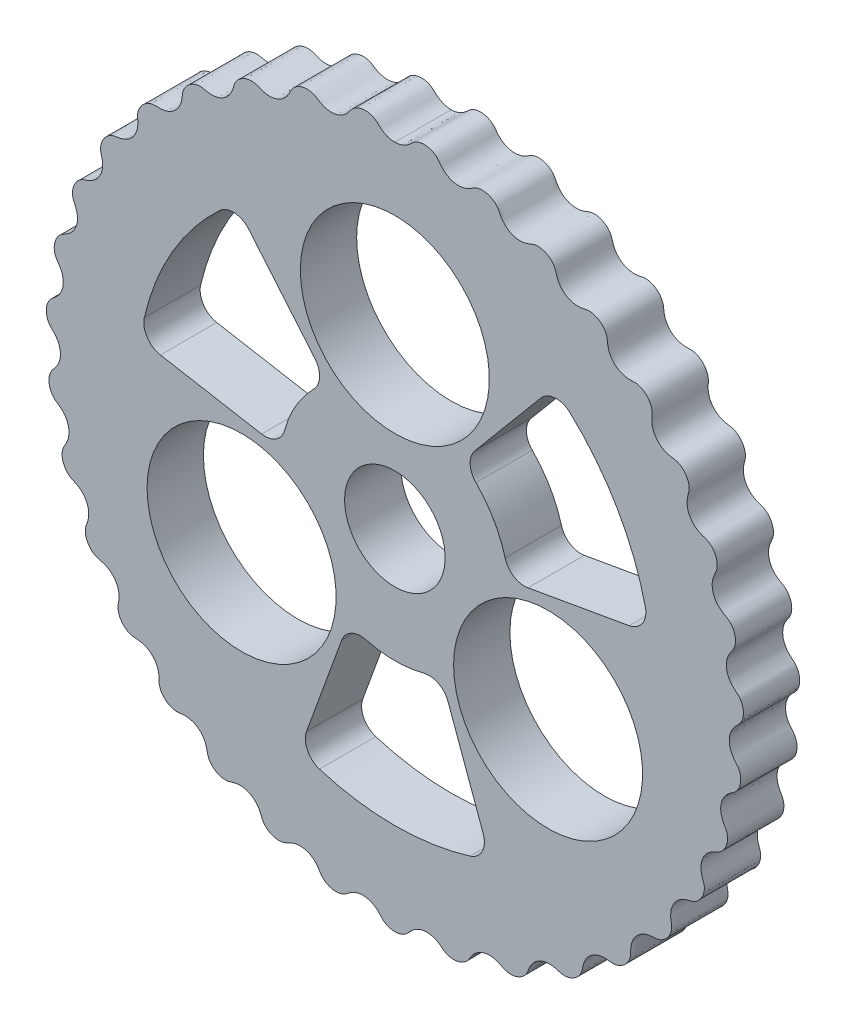
SolidWorks part; units mm, degrees
ref_plane "Plan de face" through (0, 0, 0) normal (0, 0, 1) x (1, 0, 0)
ref_plane "Plan de dessus" through (0, 0, 0) normal (0, 1, 0) x (1, 0, 0)
ref_plane "Plan de droite" through (0, 0, 0) normal (1, 0, 0) x (0, 0, -1)
sketch "Esquisse2" plane through (0, 0, 0) normal (0, 0, 1) x (1, 0, 0)
  line L0 (0, 83.25) -> (0, -86.75) construction
  spline S0 degree 4 poles (-20.3137, 83.5438) (-20.0885, 83.4614) (-19.6527, 83.2536) (-19.0693, 82.8311) (-18.2349, 82.3525) (-17.2735, 81.983) (-16.1925, 81.7883) (-14.9881, 81.8271) (-13.7247, 82.1788) (-12.6769, 82.7766) (-11.9374, 83.4413) (-11.4554, 84.0103) (-11.1542, 84.4115) (-10.918, 84.7359) (-10.664, 85.0472) (-10.378, 85.33) (-9.9202, 85.6954) (-9.2467, 86.0747) (-8.4309, 86.3423) (-7.4979, 86.4492) (-6.664, 86.3976) (-5.946, 86.2408) (-5.3028, 85.9831) (-4.7473, 85.642) (-4.2931, 85.2384) (-3.8888, 84.8455) (-3.459, 84.4786) (-3.0017, 84.147) (-2.5141, 83.861) (-2.0006, 83.6244) (-1.5285, 83.4635) (-1.1447, 83.3693) (-0.8579, 83.3179) (-0.6742, 83.2917) (-0.5261, 83.2749) (-0.3717, 83.2623) (-0.211, 83.2539) (-0.0515, 83.2494) (0.0802, 83.2498) (0.2676, 83.2558) (0.4627, 83.2686) (0.6454, 83.2876) (0.826, 83.313) (1.053, 83.3525) (1.3236, 83.4124) (1.6338, 83.5002) (1.9815, 83.6243) (2.3197, 83.7715) (2.6623, 83.9482) (3.006, 84.1564) (3.3481, 84.3972) (3.686, 84.6706) (4.0086, 84.9618) (4.3218, 85.2626) (4.6475, 85.5509) (5.0042, 85.8008) (5.4202, 86.0257) (5.8955, 86.2129) (6.5687, 86.3866) (7.4412, 86.4615) (8.311, 86.3655) (9.1397, 86.1038) (9.7424, 85.796) (10.151, 85.5199) (10.4937, 85.2237) (10.774, 84.9205) (11.0235, 84.5922) (11.2662, 84.2593) (11.5832, 83.8531) (11.979, 83.4145) (12.4759, 82.9699) (13.2366, 82.4526) (14.2315, 82.004) (15.3166, 81.7873) (16.4255, 81.823) (17.3713, 82.0294) (18.0318, 82.2747) (18.5901, 82.5587) (19.0587, 82.8445) (19.4248, 83.0864) (19.7978, 83.3187) (20.1945, 83.5089) (20.6469, 83.6634) (21.1523, 83.7693) (21.8529, 83.8268) (22.733, 83.7495) (23.5795, 83.5017) (24.3546, 83.0962) (24.9033, 82.6802) (25.2702, 82.3215) (25.5702, 81.9446) (25.8049, 81.5603) (26.0023, 81.1565) (26.2005, 80.7535) (26.4174, 80.3597) (26.6594, 79.9808) (27.0439, 79.4655) (27.6236, 78.8596) (28.4948, 78.2228) (29.5505, 77.786) (30.539, 77.6008) (31.3515, 77.5892) (31.93, 77.6458) (32.4441, 77.746) (32.894, 77.8702) (33.334, 78.0253) (33.7651, 78.2029) (34.194, 78.3861) (34.6387, 78.5298) (35.1344, 78.6217) (35.6743, 78.6503) (36.4031, 78.5923) (37.2755, 78.3642) (38.2058, 77.9072) (38.9618, 77.2791) (39.4472, 76.6783) (39.7362, 76.1701) (39.8957, 75.803) (40.0172, 75.422) (40.1233, 75.037) (40.267, 74.5587) (40.526, 73.8584) (40.9983, 72.9784) (41.7999, 72.0421) (42.9158, 71.2642) (44.0882, 70.8248) (45.0988, 70.6845) (45.9075, 70.7035) (46.5036, 70.779) (46.9756, 70.8691) (47.4431, 70.9783) (47.916, 71.066) (48.4394, 71.0935) (49.0036, 71.044) (49.755, 70.8682) (50.6104, 70.4877) (51.4678, 69.8675) (52.1115, 69.1107) (52.4843, 68.4444) (52.6828, 67.9015) (52.7791, 67.5175) (52.835, 67.1259) (52.8708, 66.7325) (52.9232, 66.2414) (53.0437, 65.5132) (53.3338, 64.5701) (53.9376, 63.4917) (54.7753, 62.62) (55.6308, 62.0456) (56.3655, 61.7153) (56.9231, 61.5369) (57.4475, 61.4244) (57.931, 61.362) (58.4177, 61.3375) (58.9048, 61.3434) (59.3909, 61.3682) (59.8787, 61.3658) (60.3981, 61.2926) (60.9369, 61.1388) (61.6269, 60.8331) (62.3688, 60.3255) (63.0708, 59.6038) (63.5998, 58.7296) (63.8644, 57.9843) (63.9663, 57.3811) (63.9848, 56.947) (63.9698, 56.6) (63.94, 56.2542) (63.9134, 55.9081) (63.8937, 55.4498) (63.9073, 54.879) (63.9959, 54.2007) (64.2091, 53.4336) (64.591, 52.5716) (65.2092, 51.6703) (66.0497, 50.8918) (66.977, 50.3664) (67.7656, 50.0812) (68.3633, 49.9344) (68.8481, 49.8488) (69.3357, 49.7851) (69.8212, 49.7012) (70.3267, 49.5419) (70.8374, 49.2975) (71.4721, 48.8748) (72.1676, 48.1961) (72.7045, 47.3755) (73.0504, 46.4563) (73.181, 45.6819) (73.1929, 45.0999) (73.1234, 44.5605) (72.996, 44.0727) (72.8633, 43.5871) (72.7569, 43.0942) (72.6693, 42.4701) (72.6457, 41.6335) (72.793, 40.5974) (73.2465, 39.4197) (74.0267, 38.3218) (74.9452, 37.5402) (75.8772, 37.0341) (76.7308, 36.7177) (77.4661, 36.5009) (78.227, 36.0981) (78.9429, 35.4726) (79.5823, 34.6046) (79.986, 33.6393) (80.1619, 32.7355) (80.1672, 31.9753) (80.0922, 31.4163) (79.9495, 30.9076) (79.7547, 30.4569) (79.5397, 30.0165) (79.3437, 29.5668) (79.1355, 28.9899) (78.9772, 28.3453) (78.8963, 27.6363) (78.9244, 26.7027) (79.1016, 25.8294) (79.4422, 24.9753) (79.9467, 24.1775) (80.4681, 23.5715) (80.9852, 23.1195) (81.4546, 22.7905) (81.8489, 22.5525) (82.1532, 22.3829) (82.4595, 22.2168) (82.7592, 22.0387) (83.1139, 21.785) (83.5647, 21.3681) (84.0449, 20.7358) (84.4825, 19.819) (84.6995, 18.8474) (84.7206, 17.9654) (84.6084, 17.239) (84.4534, 16.7146) (84.2439, 16.2464) (83.9922, 15.8394) (83.7098, 15.4544) (83.4372, 15.0623) (83.1871, 14.6551) (82.9678, 14.2304) (82.7606, 13.7358) (82.5854, 13.1672) (82.4336, 12.3496) (82.4248, 11.2888) (82.6839, 10.0825) (83.2529, 8.9651) (83.8789, 8.1973) (84.4206, 7.6917) (84.8024, 7.3755) (85.1123, 7.1282) (85.4105, 6.8662) (85.6804, 6.5746) (86.0275, 6.1096) (86.3818, 5.43) (86.6614, 4.475) (86.7087, 3.4173) (86.5573, 2.4948) (86.2931, 1.7725) (86.0266, 1.2751) (85.7184, 0.8535) (85.3873, 0.5069) (85.0398, 0.1781) (84.7049, -0.1641) (84.3133, -0.6169) (83.8506, -1.2769) (83.4074, -2.192) (83.1244, -3.3945) (83.1444, -4.7249) (83.4597, -5.8989) (83.9124, -6.7793) (84.3511, -7.3969) (84.6875, -7.8056) (84.9662, -8.124) (85.2344, -8.4522) (85.4662, -8.8075) (85.6709, -9.2162) (85.8377, -9.6771) (85.9878, -10.322) (86.047, -11.1841) (85.9354, -12.0584) (85.6498, -12.9043) (85.2998, -13.5432) (84.9814, -13.9777) (84.6345, -14.341) (84.2723, -14.6339) (83.885, -14.8907) (83.5002, -15.1509) (83.1287, -15.4306) (82.7773, -15.7351) (82.4101, -16.1059) (82.0431, -16.554) (81.6029, -17.2336) (81.189, -18.1997) (80.9597, -19.4168) (81.0484, -20.5804) (81.2942, -21.4613) (81.5488, -22.0703) (81.7297, -22.4376) (81.929, -22.7949) (82.1387, -23.1461) (82.3387, -23.5033) (82.5022, -23.8792) (82.6351, -24.3087) (82.724, -24.79) (82.7659, -25.4603) (82.6773, -26.3225) (82.4205, -27.159) (82.0044, -27.9321) (81.5737, -28.4843) (81.2095, -28.8478) (80.834, -29.1409) (80.4591, -29.3683) (80.0618, -29.5526) (79.6595, -29.7239) (79.2631, -29.9093) (78.8776, -30.1167) (78.4425, -30.3907) (77.9727, -30.7497) (77.3572, -31.343) (76.7116, -32.2435) (76.2188, -33.4327) (76.0726, -34.6266) (76.144, -35.5492) (76.2791, -36.2031) (76.3885, -36.6023) (76.5195, -36.9948) (76.6639, -37.3823) (76.8021, -37.7723) (76.9032, -38.1743) (76.9638, -38.6249) (76.971, -39.1198) (76.8975, -39.7951) (76.661, -40.6325) (76.2634, -41.4121) (75.7225, -42.0992) (75.2099, -42.5651) (74.7944, -42.8591) (74.3799, -43.0835) (73.9771, -43.2449) (73.5589, -43.3593) (73.1368, -43.4547) (72.6123, -43.5889) (71.8522, -43.8423) (70.9026, -44.3287) (69.8838, -45.1952) (69.1571, -46.2806) (68.7651, -47.3249) (68.5949, -48.2706) (68.5678, -48.9695) (68.614, -49.5897) (68.6948, -50.1288) (68.7733, -50.5574) (68.8365, -50.9892) (68.8509, -51.426) (68.8113, -51.899) (68.7071, -52.401) (68.4823, -53.0616) (68.0653, -53.8328) (67.5073, -54.507) (66.8344, -55.0551) (66.2488, -55.389) (65.7956, -55.579) (65.3619, -55.7031) (64.9562, -55.7722) (64.4439, -55.8074) (63.9312, -55.828) (63.4201, -55.8845) (62.6688, -56.03) (61.7962, -56.3159) (60.778, -56.89) (59.8937, -57.7585) (59.3216, -58.6389) (59.0023, -59.3799) (58.8341, -59.9319) (58.7296, -60.4413) (58.6711, -60.9009) (58.6439, -61.3634) (58.6396, -61.8262) (58.6376, -62.2894) (58.5904, -62.7511) (58.4766, -63.2384) (58.2881, -63.7411) (57.9471, -64.3818) (57.3976, -65.084) (56.7284, -65.6575) (55.9745, -66.0819) (55.3505, -66.311) (54.8718, -66.4244) (54.416, -66.4769) (53.9901, -66.477) (53.567, -66.4322) (53.1461, -66.375) (52.6175, -66.3205) (52.0248, -66.3026) (51.3715, -66.3529) (50.5067, -66.5334) (49.5592, -66.8996) (48.7021, -67.46) (47.9831, -68.1872) (47.5234, -68.843) (47.247, -69.3482) (47.041, -69.8278) (46.8903, -70.2713) (46.772, -70.7243) (46.6788, -71.1829) (46.5972, -71.6436) (46.4812, -72.0978) (46.2921, -72.5712) (46.0218, -73.0501) (45.5688, -73.6459) (44.8902, -74.2638) (43.9891, -74.7977) (42.9475, -75.1154) (42.0775, -75.1772) (41.3992, -75.0867) (40.9195, -74.953) (40.5411, -74.8303) (40.0648, -74.6861) (39.341, -74.5146) (38.3509, -74.4195) (37.0745, -74.5714) (35.8887, -75.0526) (34.9757, -75.6992) (34.3645, -76.3343) (33.9963, -76.8217) (33.7177, -77.2755) (33.5091, -77.6793) (33.327, -78.0958) (33.1647, -78.5199) (33.0016, -78.9441) (32.7967, -79.3507) (32.5228, -79.7583) (32.1761, -80.1551) (31.6425, -80.6272) (30.8921, -81.09) (29.9399, -81.4439) (28.9825, -81.5629) (28.2239, -81.5097) (27.6629, -81.3793) (27.2901, -81.2504) (26.933, -81.0836) (26.5861, -80.8976) (26.1493, -80.6708) (25.4789, -80.3691) (24.5372, -80.0882) (23.3077, -79.9908) (22.1183, -80.2017) (21.1643, -80.5936) (20.3752, -81.0873) (19.8323, -81.5467) (19.3853, -82.0342) (19.0215, -82.5253) (18.7561, -82.936) (18.5081, -83.3567) (18.2383, -83.7651) (17.8918, -84.1612) (17.4665, -84.529) (16.8302, -84.9398) (16.0633, -85.2546) (15.2201, -85.4334) (14.328, -85.4518) (13.5689, -85.3442) (12.873, -85.1185) (12.2622, -84.7834) (11.7499, -84.3712) (11.2593, -83.9912) (10.7379, -83.6518) (10.1856, -83.3662) (9.6051, -83.1421) (9.0031, -82.9846) (8.2142, -82.8724) (7.4052, -82.8868) (6.5996, -83.0341) (5.7411, -83.3421) (5.1148, -83.6737) (4.5689, -84.0602) (4.0996, -84.4775) (3.749, -84.8375) (3.4186, -85.2151) (3.0815, -85.5878) (2.7318, -85.8864) (2.3863, -86.1168) (2.0591, -86.2923) (1.7595, -86.4244) (1.4896, -86.5202) (1.2539, -86.5885) (1.015, -86.6458) (0.8135, -86.6843) (0.6149, -86.7138) (0.4086, -86.7342) (0.2334, -86.745) (0.0699, -86.7503) (-0.0518, -86.7505) (-0.2345, -86.7452) (-0.4665, -86.7309) (-0.6728, -86.7064) (-0.8821, -86.6716) (-1.0908, -86.6285) (-1.2978, -86.5772) (-1.5354, -86.5051) (-1.8017, -86.4061) (-2.0878, -86.278) (-2.3893, -86.1144) (-2.6994, -85.9078) (-3.0086, -85.6504) (-3.2886, -85.3621) (-3.5528, -85.06) (-3.8894, -84.6877) (-4.299, -84.2858) (-4.8034, -83.8813) (-5.5626, -83.4161) (-6.4905, -83.0419) (-7.6131, -82.8396) (-8.8327, -82.9146) (-9.796, -83.1878) (-10.535, -83.5359) (-11.0755, -83.8686) (-11.488, -84.165) (-11.8837, -84.482) (-12.2887, -84.7889) (-12.7554, -85.052) (-13.2795, -85.2553) (-14.0025, -85.4253) (-14.8826, -85.47) (-15.8646, -85.3259) (-16.8095, -84.96) (-17.5493, -84.4853) (-18.0552, -83.9977) (-18.369, -83.5763) (-18.6423, -83.1296) (-18.8229, -82.8307) (-18.9676, -82.6125) (-19.0683, -82.4698) knots 0 0 0 0 0 0.002755 0.005511 0.008266 0.011022 0.014533 0.018044 0.021993 0.025941 0.028246 0.029399 0.030552 0.031705 0.032857 0.03401 0.035163 0.038424 0.041684 0.043786 0.045887 0.047989 0.050091 0.051711 0.053332 0.054953 0.056574 0.058195 0.059815 0.061436 0.063057 0.063918 0.064349 0.064779 0.06521 0.06564 0.066071 0.066501 0.067031 0.06756 0.06809 0.068619 0.069149 0.069678 0.070737 0.071796 0.072855 0.073914 0.074973 0.07622 0.077468 0.078716 0.079964 0.081212 0.08246 0.083707 0.084955 0.086635 0.088314 0.091673 0.094958 0.096601 0.098243 0.099427 0.100611 0.101794 0.102978 0.104162 0.105346 0.107713 0.109756 0.111799 0.115885 0.120169 0.122311 0.124453 0.126974 0.128235 0.129496 0.130757 0.132018 0.133278 0.134539 0.136237 0.137935 0.141332 0.144631 0.14628 0.14793 0.14922 0.150511 0.151801 0.153092 0.154382 0.155673 0.156963 0.158253 0.161762 0.16527 0.169256 0.171249 0.173242 0.174582 0.175921 0.17726 0.1786 0.179939 0.181278 0.182618 0.183957 0.185715 0.187473 0.19099 0.194252 0.197514 0.198662 0.199809 0.200957 0.202104 0.203252 0.204399 0.206694 0.210675 0.214655 0.218407 0.222158 0.224917 0.226297 0.227676 0.229056 0.230435 0.231815 0.233194 0.235058 0.236921 0.240648 0.243874 0.247099 0.248234 0.249369 0.250503 0.251638 0.252773 0.253908 0.256178 0.26011 0.264043 0.267959 0.269917 0.271876 0.273274 0.274673 0.276071 0.27747 0.278869 0.280267 0.281666 0.283065 0.284875 0.286686 0.290307 0.293323 0.29634 0.298334 0.299331 0.300328 0.301325 0.302322 0.303319 0.304316 0.306595 0.308874 0.311153 0.313432 0.317388 0.321344 0.32417 0.325583 0.326996 0.328409 0.329822 0.331235 0.332648 0.334478 0.336307 0.339965 0.343736 0.345621 0.347507 0.348954 0.350401 0.351847 0.353294 0.354741 0.356188 0.359082 0.362879 0.366677 0.370538 0.374399 0.376596 0.378794 0.380991 0.383188 0.386406 0.389624 0.39327 0.395093 0.396916 0.398324 0.399733 0.401141 0.402549 0.403957 0.405366 0.408182 0.410154 0.412125 0.416068 0.418356 0.420644 0.422932 0.42522 0.426221 0.427222 0.428222 0.429223 0.430224 0.431224 0.433226 0.436254 0.439282 0.442804 0.444566 0.446327 0.447698 0.44907 0.450441 0.451813 0.453184 0.454556 0.455927 0.457299 0.459338 0.461377 0.465456 0.469405 0.473353 0.475631 0.47677 0.477909 0.479048 0.480187 0.481326 0.482465 0.485703 0.48894 0.492655 0.494512 0.496369 0.497743 0.499118 0.500493 0.501867 0.503242 0.504617 0.507366 0.511104 0.514843 0.518671 0.522499 0.524931 0.526147 0.527363 0.528578 0.529794 0.53101 0.532226 0.533819 0.535413 0.538599 0.542103 0.543855 0.545607 0.546941 0.548276 0.549611 0.550945 0.55228 0.553614 0.554949 0.556283 0.558269 0.560256 0.564228 0.568282 0.572336 0.573512 0.574687 0.575862 0.577037 0.578212 0.579387 0.580562 0.581737 0.583367 0.584997 0.588257 0.591641 0.593333 0.595025 0.596281 0.597538 0.598794 0.600051 0.601307 0.602564 0.60382 0.605077 0.607211 0.609344 0.613612 0.617714 0.621816 0.623004 0.624192 0.62538 0.626569 0.627757 0.628945 0.630133 0.631321 0.63297 0.634618 0.637915 0.641262 0.642935 0.644609 0.645852 0.647096 0.648339 0.649583 0.650826 0.65207 0.654557 0.658777 0.662996 0.667248 0.669374 0.671499 0.674004 0.675256 0.676508 0.67776 0.679012 0.680264 0.681517 0.683202 0.684888 0.68826 0.691532 0.693168 0.694804 0.695984 0.697163 0.698343 0.699522 0.701881 0.70306 0.70424 0.70831 0.71238 0.716338 0.718317 0.720297 0.721626 0.722956 0.724286 0.725616 0.726945 0.728275 0.729605 0.730935 0.732681 0.734426 0.737918 0.741116 0.742715 0.744314 0.745535 0.746756 0.747976 0.749197 0.750417 0.751638 0.754079 0.756001 0.757922 0.761765 0.765682 0.76764 0.769599 0.770943 0.772287 0.773631 0.774975 0.776319 0.777663 0.779007 0.780351 0.782157 0.783963 0.787576 0.790826 0.794076 0.796362 0.797506 0.798649 0.799792 0.800935 0.803222 0.807186 0.811151 0.815545 0.817743 0.81994 0.821245 0.822549 0.823854 0.825159 0.826464 0.827768 0.829073 0.830378 0.832092 0.833806 0.837234 0.840447 0.84366 0.844791 0.845922 0.847052 0.848183 0.849314 0.850445 0.852706 0.856622 0.860539 0.864468 0.866433 0.868398 0.871205 0.872608 0.874012 0.875415 0.876819 0.878222 0.879626 0.881442 0.883259 0.886893 0.889085 0.891277 0.89347 0.895662 0.897445 0.899228 0.901012 0.902795 0.904578 0.906362 0.908145 0.909928 0.913714 0.915606 0.917499 0.920383 0.921825 0.923267 0.924709 0.926151 0.927592 0.929034 0.929974 0.930914 0.931853 0.932793 0.933263 0.933732 0.934672 0.935142 0.935612 0.936081 0.936551 0.936959 0.937367 0.938182 0.938997 0.939405 0.939812 0.940628 0.941443 0.942258 0.943074 0.944227 0.94538 0.946533 0.947686 0.948839 0.949992 0.952298 0.954273 0.956247 0.960196 0.963723 0.967249 0.970164 0.971621 0.973078 0.974536 0.975993 0.97745 0.978908 0.980669 0.982431 0.985955 0.988966 0.991977 0.993983 0.995988 0.996991 0.997994 1 1 1 1 1 construction
  spline S1 degree 4 poles (0, 83.25) (0.0401, 83.25) (0.1201, 83.2511) (0.2676, 83.2558) (0.4627, 83.2686) (0.6454, 83.2876) (0.826, 83.313) (1.053, 83.3525) (1.3236, 83.4124) (1.6338, 83.5002) (1.9815, 83.6243) (2.3197, 83.7715) (2.6623, 83.9482) (3.006, 84.1564) (3.3481, 84.3972) (3.686, 84.6706) (4.0086, 84.9618) (4.3218, 85.2626) (4.6475, 85.5509) (5.0042, 85.8008) (5.4202, 86.0257) (5.8955, 86.2129) (6.5687, 86.3866) (7.4412, 86.4615) (8.311, 86.3655) (9.1397, 86.1038) (9.7424, 85.796) (10.151, 85.5199) (10.4937, 85.2237) (10.774, 84.9205) (11.0235, 84.5922) (11.2662, 84.2593) (11.5832, 83.8531) (11.979, 83.4145) (12.4759, 82.9699) (13.2366, 82.4526) (14.2315, 82.004) (15.3166, 81.7873) (16.4255, 81.823) (17.3713, 82.0294) (18.0318, 82.2747) (18.5901, 82.5587) (19.0587, 82.8445) (19.4248, 83.0864) (19.7978, 83.3187) (20.1945, 83.5089) (20.6469, 83.6634) (21.1523, 83.7693) (21.8529, 83.8268) (22.733, 83.7495) (23.5795, 83.5017) (24.3546, 83.0962) (24.9033, 82.6802) (25.2702, 82.3215) (25.5702, 81.9446) (25.8049, 81.5603) (26.0023, 81.1565) (26.2005, 80.7535) (26.4174, 80.3597) (26.6594, 79.9808) (27.0439, 79.4655) (27.6236, 78.8596) (28.4948, 78.2228) (29.5505, 77.786) (30.539, 77.6008) (31.3515, 77.5892) (31.93, 77.6458) (32.4441, 77.746) (32.894, 77.8702) (33.334, 78.0253) (33.7651, 78.2029) (34.194, 78.3861) (34.6387, 78.5298) (35.1344, 78.6217) (35.6743, 78.6503) (36.4031, 78.5923) (37.2755, 78.3642) (38.2058, 77.9072) (38.9618, 77.2791) (39.4472, 76.6783) (39.7362, 76.1701) (39.8957, 75.803) (40.0172, 75.422) (40.1233, 75.037) (40.267, 74.5587) (40.526, 73.8584) (40.9983, 72.9784) (41.7999, 72.0421) (42.9158, 71.2642) (44.0882, 70.8248) (45.0988, 70.6845) (45.9075, 70.7035) (46.5036, 70.779) (46.9756, 70.8691) (47.4431, 70.9783) (47.916, 71.066) (48.4394, 71.0935) (49.0036, 71.044) (49.755, 70.8682) (50.6104, 70.4877) (51.4678, 69.8675) (52.1115, 69.1107) (52.4843, 68.4444) (52.6828, 67.9015) (52.7791, 67.5175) (52.835, 67.1259) (52.8708, 66.7325) (52.9232, 66.2414) (53.0437, 65.5132) (53.3338, 64.5701) (53.9376, 63.4917) (54.7753, 62.62) (55.6308, 62.0456) (56.3655, 61.7153) (56.9231, 61.5369) (57.4475, 61.4244) (57.931, 61.362) (58.4177, 61.3375) (58.9048, 61.3434) (59.3909, 61.3682) (59.8787, 61.3658) (60.3981, 61.2926) (60.9369, 61.1388) (61.6269, 60.8331) (62.3688, 60.3255) (63.0708, 59.6038) (63.5998, 58.7296) (63.8644, 57.9843) (63.9663, 57.3811) (63.9848, 56.947) (63.9698, 56.6) (63.94, 56.2542) (63.9134, 55.9081) (63.8937, 55.4498) (63.9073, 54.879) (63.9959, 54.2007) (64.2091, 53.4336) (64.591, 52.5716) (65.2092, 51.6703) (66.0497, 50.8918) (66.977, 50.3664) (67.7656, 50.0812) (68.3633, 49.9344) (68.8481, 49.8488) (69.3357, 49.7851) (69.8212, 49.7012) (70.3267, 49.5419) (70.8374, 49.2975) (71.4721, 48.8748) (72.1676, 48.1961) (72.7045, 47.3755) (73.0504, 46.4563) (73.181, 45.6819) (73.1929, 45.0999) (73.1234, 44.5605) (72.996, 44.0727) (72.8633, 43.5871) (72.7569, 43.0942) (72.6693, 42.4701) (72.6457, 41.6335) (72.793, 40.5974) (73.2465, 39.4197) (74.0267, 38.3218) (74.9452, 37.5402) (75.8772, 37.0341) (76.7308, 36.7177) (77.4661, 36.5009) (78.227, 36.0981) (78.9429, 35.4726) (79.5823, 34.6046) (79.986, 33.6393) (80.1619, 32.7355) (80.1672, 31.9753) (80.0922, 31.4163) (79.9495, 30.9076) (79.7547, 30.4569) (79.5397, 30.0165) (79.3437, 29.5668) (79.1355, 28.9899) (78.9772, 28.3453) (78.8963, 27.6363) (78.9244, 26.7027) (79.1016, 25.8294) (79.4422, 24.9753) (79.9467, 24.1775) (80.4681, 23.5715) (80.9852, 23.1195) (81.4546, 22.7905) (81.8489, 22.5525) (82.1532, 22.3829) (82.4595, 22.2168) (82.7592, 22.0387) (83.1139, 21.785) (83.5647, 21.3681) (84.0449, 20.7358) (84.4825, 19.819) (84.6995, 18.8474) (84.7206, 17.9654) (84.6084, 17.239) (84.4534, 16.7146) (84.2439, 16.2464) (83.9922, 15.8394) (83.7098, 15.4544) (83.4372, 15.0623) (83.1871, 14.6551) (82.9678, 14.2304) (82.7606, 13.7358) (82.5854, 13.1672) (82.4336, 12.3496) (82.4248, 11.2888) (82.6839, 10.0825) (83.2529, 8.9651) (83.8789, 8.1973) (84.4206, 7.6917) (84.8024, 7.3755) (85.1123, 7.1282) (85.4105, 6.8662) (85.6804, 6.5746) (86.0275, 6.1096) (86.3818, 5.43) (86.6614, 4.475) (86.7087, 3.4173) (86.5573, 2.4948) (86.2931, 1.7725) (86.0266, 1.2751) (85.7184, 0.8535) (85.3873, 0.5069) (85.0398, 0.1781) (84.7049, -0.1641) (84.3133, -0.6169) (83.8506, -1.2769) (83.4074, -2.192) (83.1244, -3.3945) (83.1444, -4.7249) (83.4597, -5.8989) (83.9124, -6.7793) (84.3511, -7.3969) (84.6875, -7.8056) (84.9662, -8.124) (85.2344, -8.4522) (85.4662, -8.8075) (85.6709, -9.2162) (85.8377, -9.6771) (85.9878, -10.322) (86.047, -11.1841) (85.9354, -12.0584) (85.6498, -12.9043) (85.2998, -13.5432) (84.9814, -13.9777) (84.6345, -14.341) (84.2723, -14.6339) (83.885, -14.8907) (83.5002, -15.1509) (83.1287, -15.4306) (82.7773, -15.7351) (82.4101, -16.1059) (82.0431, -16.554) (81.6029, -17.2336) (81.189, -18.1997) (80.9597, -19.4168) (81.0484, -20.5804) (81.2942, -21.4613) (81.5488, -22.0703) (81.7297, -22.4376) (81.929, -22.7949) (82.1387, -23.1461) (82.3387, -23.5033) (82.5022, -23.8792) (82.6351, -24.3087) (82.724, -24.79) (82.7659, -25.4603) (82.6773, -26.3225) (82.4205, -27.159) (82.0044, -27.9321) (81.5737, -28.4843) (81.2095, -28.8478) (80.834, -29.1409) (80.4591, -29.3683) (80.0618, -29.5526) (79.6595, -29.7239) (79.2631, -29.9093) (78.8776, -30.1167) (78.4425, -30.3907) (77.9727, -30.7497) (77.3572, -31.343) (76.7116, -32.2435) (76.2188, -33.4327) (76.0726, -34.6266) (76.144, -35.5492) (76.2791, -36.2031) (76.3885, -36.6023) (76.5195, -36.9948) (76.6639, -37.3823) (76.8021, -37.7723) (76.9032, -38.1743) (76.9638, -38.6249) (76.971, -39.1198) (76.8975, -39.7951) (76.661, -40.6325) (76.2634, -41.4121) (75.7225, -42.0992) (75.2099, -42.5651) (74.7944, -42.8591) (74.3799, -43.0835) (73.9771, -43.2449) (73.5589, -43.3593) (73.1368, -43.4547) (72.6123, -43.5889) (71.8522, -43.8423) (70.9026, -44.3287) (69.8838, -45.1952) (69.1571, -46.2806) (68.7651, -47.3249) (68.5949, -48.2706) (68.5678, -48.9695) (68.614, -49.5897) (68.6948, -50.1288) (68.7733, -50.5574) (68.8365, -50.9892) (68.8509, -51.426) (68.8113, -51.899) (68.7071, -52.401) (68.4823, -53.0616) (68.0653, -53.8328) (67.5073, -54.507) (66.8344, -55.0551) (66.2488, -55.389) (65.7956, -55.579) (65.3619, -55.7031) (64.9562, -55.7722) (64.4439, -55.8074) (63.9312, -55.828) (63.4201, -55.8845) (62.6688, -56.03) (61.7962, -56.3159) (60.778, -56.89) (59.8937, -57.7585) (59.3216, -58.6389) (59.0023, -59.3799) (58.8341, -59.9319) (58.7296, -60.4413) (58.6711, -60.9009) (58.6439, -61.3634) (58.6396, -61.8262) (58.6376, -62.2894) (58.5904, -62.7511) (58.4766, -63.2384) (58.2881, -63.7411) (57.9471, -64.3818) (57.3976, -65.084) (56.7284, -65.6575) (55.9745, -66.0819) (55.3505, -66.311) (54.8718, -66.4244) (54.416, -66.4769) (53.9901, -66.477) (53.567, -66.4322) (53.1461, -66.375) (52.6175, -66.3205) (52.0248, -66.3026) (51.3715, -66.3529) (50.5067, -66.5334) (49.5592, -66.8996) (48.7021, -67.46) (47.9831, -68.1872) (47.5234, -68.843) (47.247, -69.3482) (47.041, -69.8278) (46.8903, -70.2713) (46.772, -70.7243) (46.6788, -71.1829) (46.5972, -71.6436) (46.4812, -72.0978) (46.2921, -72.5712) (46.0218, -73.0501) (45.5688, -73.6459) (44.8902, -74.2638) (43.9891, -74.7977) (42.9475, -75.1154) (42.0775, -75.1772) (41.3992, -75.0867) (40.9195, -74.953) (40.5411, -74.8303) (40.0648, -74.6861) (39.341, -74.5146) (38.3509, -74.4195) (37.0745, -74.5714) (35.8887, -75.0526) (34.9757, -75.6992) (34.3645, -76.3343) (33.9963, -76.8217) (33.7177, -77.2755) (33.5091, -77.6793) (33.327, -78.0958) (33.1647, -78.5199) (33.0016, -78.9441) (32.7967, -79.3507) (32.5228, -79.7583) (32.1761, -80.1551) (31.6425, -80.6272) (30.8921, -81.09) (29.9399, -81.4439) (28.9825, -81.5629) (28.2239, -81.5097) (27.6629, -81.3793) (27.2901, -81.2504) (26.933, -81.0836) (26.5861, -80.8976) (26.1493, -80.6708) (25.4789, -80.3691) (24.5372, -80.0882) (23.3077, -79.9908) (22.1183, -80.2017) (21.1643, -80.5936) (20.3752, -81.0873) (19.8323, -81.5467) (19.3853, -82.0342) (19.0215, -82.5253) (18.7561, -82.936) (18.5081, -83.3567) (18.2383, -83.7651) (17.8918, -84.1612) (17.4665, -84.529) (16.8302, -84.9398) (16.0633, -85.2546) (15.2201, -85.4334) (14.328, -85.4518) (13.5689, -85.3442) (12.873, -85.1185) (12.2622, -84.7834) (11.7499, -84.3712) (11.2593, -83.9912) (10.7379, -83.6518) (10.1856, -83.3662) (9.6051, -83.1421) (9.0031, -82.9846) (8.2142, -82.8724) (7.4052, -82.8868) (6.5996, -83.0341) (5.7411, -83.3421) (5.1148, -83.6737) (4.5689, -84.0602) (4.0996, -84.4775) (3.749, -84.8375) (3.4186, -85.2151) (3.0815, -85.5878) (2.7318, -85.8864) (2.3863, -86.1168) (2.0591, -86.2923) (1.7595, -86.4244) (1.4896, -86.5202) (1.2539, -86.5885) (1.015, -86.6458) (0.8135, -86.6843) (0.6149, -86.7138) (0.4086, -86.7342) (0.2334, -86.745) (0.1066, -86.7491) (0.0356, -86.75) (0, -86.75) knots 0.066501 0.066501 0.066501 0.066501 0.066501 0.067031 0.06756 0.06809 0.068619 0.069149 0.069678 0.070737 0.071796 0.072855 0.073914 0.074973 0.07622 0.077468 0.078716 0.079964 0.081212 0.08246 0.083707 0.084955 0.086635 0.088314 0.091673 0.094958 0.096601 0.098243 0.099427 0.100611 0.101794 0.102978 0.104162 0.105346 0.107713 0.109756 0.111799 0.115885 0.120169 0.122311 0.124453 0.126974 0.128235 0.129496 0.130757 0.132018 0.133278 0.134539 0.136237 0.137935 0.141332 0.144631 0.14628 0.14793 0.14922 0.150511 0.151801 0.153092 0.154382 0.155673 0.156963 0.158253 0.161762 0.16527 0.169256 0.171249 0.173242 0.174582 0.175921 0.17726 0.1786 0.179939 0.181278 0.182618 0.183957 0.185715 0.187473 0.19099 0.194252 0.197514 0.198662 0.199809 0.200957 0.202104 0.203252 0.204399 0.206694 0.210675 0.214655 0.218407 0.222158 0.224917 0.226297 0.227676 0.229056 0.230435 0.231815 0.233194 0.235058 0.236921 0.240648 0.243874 0.247099 0.248234 0.249369 0.250503 0.251638 0.252773 0.253908 0.256178 0.26011 0.264043 0.267959 0.269917 0.271876 0.273274 0.274673 0.276071 0.27747 0.278869 0.280267 0.281666 0.283065 0.284875 0.286686 0.290307 0.293323 0.29634 0.298334 0.299331 0.300328 0.301325 0.302322 0.303319 0.304316 0.306595 0.308874 0.311153 0.313432 0.317388 0.321344 0.32417 0.325583 0.326996 0.328409 0.329822 0.331235 0.332648 0.334478 0.336307 0.339965 0.343736 0.345621 0.347507 0.348954 0.350401 0.351847 0.353294 0.354741 0.356188 0.359082 0.362879 0.366677 0.370538 0.374399 0.376596 0.378794 0.380991 0.383188 0.386406 0.389624 0.39327 0.395093 0.396916 0.398324 0.399733 0.401141 0.402549 0.403957 0.405366 0.408182 0.410154 0.412125 0.416068 0.418356 0.420644 0.422932 0.42522 0.426221 0.427222 0.428222 0.429223 0.430224 0.431224 0.433226 0.436254 0.439282 0.442804 0.444566 0.446327 0.447698 0.44907 0.450441 0.451813 0.453184 0.454556 0.455927 0.457299 0.459338 0.461377 0.465456 0.469405 0.473353 0.475631 0.47677 0.477909 0.479048 0.480187 0.481326 0.482465 0.485703 0.48894 0.492655 0.494512 0.496369 0.497743 0.499118 0.500493 0.501867 0.503242 0.504617 0.507366 0.511104 0.514843 0.518671 0.522499 0.524931 0.526147 0.527363 0.528578 0.529794 0.53101 0.532226 0.533819 0.535413 0.538599 0.542103 0.543855 0.545607 0.546941 0.548276 0.549611 0.550945 0.55228 0.553614 0.554949 0.556283 0.558269 0.560256 0.564228 0.568282 0.572336 0.573512 0.574687 0.575862 0.577037 0.578212 0.579387 0.580562 0.581737 0.583367 0.584997 0.588257 0.591641 0.593333 0.595025 0.596281 0.597538 0.598794 0.600051 0.601307 0.602564 0.60382 0.605077 0.607211 0.609344 0.613612 0.617714 0.621816 0.623004 0.624192 0.62538 0.626569 0.627757 0.628945 0.630133 0.631321 0.63297 0.634618 0.637915 0.641262 0.642935 0.644609 0.645852 0.647096 0.648339 0.649583 0.650826 0.65207 0.654557 0.658777 0.662996 0.667248 0.669374 0.671499 0.674004 0.675256 0.676508 0.67776 0.679012 0.680264 0.681517 0.683202 0.684888 0.68826 0.691532 0.693168 0.694804 0.695984 0.697163 0.698343 0.699522 0.701881 0.70306 0.70424 0.70831 0.71238 0.716338 0.718317 0.720297 0.721626 0.722956 0.724286 0.725616 0.726945 0.728275 0.729605 0.730935 0.732681 0.734426 0.737918 0.741116 0.742715 0.744314 0.745535 0.746756 0.747976 0.749197 0.750417 0.751638 0.754079 0.756001 0.757922 0.761765 0.765682 0.76764 0.769599 0.770943 0.772287 0.773631 0.774975 0.776319 0.777663 0.779007 0.780351 0.782157 0.783963 0.787576 0.790826 0.794076 0.796362 0.797506 0.798649 0.799792 0.800935 0.803222 0.807186 0.811151 0.815545 0.817743 0.81994 0.821245 0.822549 0.823854 0.825159 0.826464 0.827768 0.829073 0.830378 0.832092 0.833806 0.837234 0.840447 0.84366 0.844791 0.845922 0.847052 0.848183 0.849314 0.850445 0.852706 0.856622 0.860539 0.864468 0.866433 0.868398 0.871205 0.872608 0.874012 0.875415 0.876819 0.878222 0.879626 0.881442 0.883259 0.886893 0.889085 0.891277 0.89347 0.895662 0.897445 0.899228 0.901012 0.902795 0.904578 0.906362 0.908145 0.909928 0.913714 0.915606 0.917499 0.920383 0.921825 0.923267 0.924709 0.926151 0.927592 0.929034 0.929974 0.930914 0.931853 0.932793 0.933263 0.933732 0.934672 0.935142 0.935612 0.936081 0.936551 0.936551 0.936551 0.936551 0.936551
  spline S2 degree 4 poles (0, 83.25) (-0.0401, 83.25) (-0.1201, 83.2511) (-0.2676, 83.2558) (-0.4627, 83.2686) (-0.6454, 83.2876) (-0.826, 83.313) (-1.053, 83.3525) (-1.3236, 83.4124) (-1.6338, 83.5002) (-1.9815, 83.6243) (-2.3197, 83.7715) (-2.6623, 83.9482) (-3.006, 84.1564) (-3.3481, 84.3972) (-3.686, 84.6706) (-4.0086, 84.9618) (-4.3218, 85.2626) (-4.6475, 85.5509) (-5.0042, 85.8008) (-5.4202, 86.0257) (-5.8955, 86.2129) (-6.5687, 86.3866) (-7.4412, 86.4615) (-8.311, 86.3655) (-9.1397, 86.1038) (-9.7424, 85.796) (-10.151, 85.5199) (-10.4937, 85.2237) (-10.774, 84.9205) (-11.0235, 84.5922) (-11.2662, 84.2593) (-11.5832, 83.8531) (-11.979, 83.4145) (-12.4759, 82.9699) (-13.2366, 82.4526) (-14.2315, 82.004) (-15.3166, 81.7873) (-16.4255, 81.823) (-17.3713, 82.0294) (-18.0318, 82.2747) (-18.5901, 82.5587) (-19.0587, 82.8445) (-19.4248, 83.0864) (-19.7978, 83.3187) (-20.1945, 83.5089) (-20.6469, 83.6634) (-21.1523, 83.7693) (-21.8529, 83.8268) (-22.733, 83.7495) (-23.5795, 83.5017) (-24.3546, 83.0962) (-24.9033, 82.6802) (-25.2702, 82.3215) (-25.5702, 81.9446) (-25.8049, 81.5603) (-26.0023, 81.1565) (-26.2005, 80.7535) (-26.4174, 80.3597) (-26.6594, 79.9808) (-27.0439, 79.4655) (-27.6236, 78.8596) (-28.4948, 78.2228) (-29.5505, 77.786) (-30.539, 77.6008) (-31.3515, 77.5892) (-31.93, 77.6458) (-32.4441, 77.746) (-32.894, 77.8702) (-33.334, 78.0253) (-33.7651, 78.2029) (-34.194, 78.3861) (-34.6387, 78.5298) (-35.1344, 78.6217) (-35.6743, 78.6503) (-36.4031, 78.5923) (-37.2755, 78.3642) (-38.2058, 77.9072) (-38.9618, 77.2791) (-39.4472, 76.6783) (-39.7362, 76.1701) (-39.8957, 75.803) (-40.0172, 75.422) (-40.1233, 75.037) (-40.267, 74.5587) (-40.526, 73.8584) (-40.9983, 72.9784) (-41.7999, 72.0421) (-42.9158, 71.2642) (-44.0882, 70.8248) (-45.0988, 70.6845) (-45.9075, 70.7035) (-46.5036, 70.779) (-46.9756, 70.8691) (-47.4431, 70.9783) (-47.916, 71.066) (-48.4394, 71.0935) (-49.0036, 71.044) (-49.755, 70.8682) (-50.6104, 70.4877) (-51.4678, 69.8675) (-52.1115, 69.1107) (-52.4843, 68.4444) (-52.6828, 67.9015) (-52.7791, 67.5175) (-52.835, 67.1259) (-52.8708, 66.7325) (-52.9232, 66.2414) (-53.0437, 65.5132) (-53.3338, 64.5701) (-53.9376, 63.4917) (-54.7753, 62.62) (-55.6308, 62.0456) (-56.3655, 61.7153) (-56.9231, 61.5369) (-57.4475, 61.4244) (-57.931, 61.362) (-58.4177, 61.3375) (-58.9048, 61.3434) (-59.3909, 61.3682) (-59.8787, 61.3658) (-60.3981, 61.2926) (-60.9369, 61.1388) (-61.6269, 60.8331) (-62.3688, 60.3255) (-63.0708, 59.6038) (-63.5998, 58.7296) (-63.8644, 57.9843) (-63.9663, 57.3811) (-63.9848, 56.947) (-63.9698, 56.6) (-63.94, 56.2542) (-63.9134, 55.9081) (-63.8937, 55.4498) (-63.9073, 54.879) (-63.9959, 54.2007) (-64.2091, 53.4336) (-64.591, 52.5716) (-65.2092, 51.6703) (-66.0497, 50.8918) (-66.977, 50.3664) (-67.7656, 50.0812) (-68.3633, 49.9344) (-68.8481, 49.8488) (-69.3357, 49.7851) (-69.8212, 49.7012) (-70.3267, 49.5419) (-70.8374, 49.2975) (-71.4721, 48.8748) (-72.1676, 48.1961) (-72.7045, 47.3755) (-73.0504, 46.4563) (-73.181, 45.6819) (-73.1929, 45.0999) (-73.1234, 44.5605) (-72.996, 44.0727) (-72.8633, 43.5871) (-72.7569, 43.0942) (-72.6693, 42.4701) (-72.6457, 41.6335) (-72.793, 40.5974) (-73.2465, 39.4197) (-74.0267, 38.3218) (-74.9452, 37.5402) (-75.8772, 37.0341) (-76.7308, 36.7177) (-77.4661, 36.5009) (-78.227, 36.0981) (-78.9429, 35.4726) (-79.5823, 34.6046) (-79.986, 33.6393) (-80.1619, 32.7355) (-80.1672, 31.9753) (-80.0922, 31.4163) (-79.9495, 30.9076) (-79.7547, 30.4569) (-79.5397, 30.0165) (-79.3437, 29.5668) (-79.1355, 28.9899) (-78.9772, 28.3453) (-78.8963, 27.6363) (-78.9244, 26.7027) (-79.1016, 25.8294) (-79.4422, 24.9753) (-79.9467, 24.1775) (-80.4681, 23.5715) (-80.9852, 23.1195) (-81.4546, 22.7905) (-81.8489, 22.5525) (-82.1532, 22.3829) (-82.4595, 22.2168) (-82.7592, 22.0387) (-83.1139, 21.785) (-83.5647, 21.3681) (-84.0449, 20.7358) (-84.4825, 19.819) (-84.6995, 18.8474) (-84.7206, 17.9654) (-84.6084, 17.239) (-84.4534, 16.7146) (-84.2439, 16.2464) (-83.9922, 15.8394) (-83.7098, 15.4544) (-83.4372, 15.0623) (-83.1871, 14.6551) (-82.9678, 14.2304) (-82.7606, 13.7358) (-82.5854, 13.1672) (-82.4336, 12.3496) (-82.4248, 11.2888) (-82.6839, 10.0825) (-83.2529, 8.9651) (-83.8789, 8.1973) (-84.4206, 7.6917) (-84.8024, 7.3755) (-85.1123, 7.1282) (-85.4105, 6.8662) (-85.6804, 6.5746) (-86.0275, 6.1096) (-86.3818, 5.43) (-86.6614, 4.475) (-86.7087, 3.4173) (-86.5573, 2.4948) (-86.2931, 1.7725) (-86.0266, 1.2751) (-85.7184, 0.8535) (-85.3873, 0.5069) (-85.0398, 0.1781) (-84.7049, -0.1641) (-84.3133, -0.6169) (-83.8506, -1.2769) (-83.4074, -2.192) (-83.1244, -3.3945) (-83.1444, -4.7249) (-83.4597, -5.8989) (-83.9124, -6.7793) (-84.3511, -7.3969) (-84.6875, -7.8056) (-84.9662, -8.124) (-85.2344, -8.4522) (-85.4662, -8.8075) (-85.6709, -9.2162) (-85.8377, -9.6771) (-85.9878, -10.322) (-86.047, -11.1841) (-85.9354, -12.0584) (-85.6498, -12.9043) (-85.2998, -13.5432) (-84.9814, -13.9777) (-84.6345, -14.341) (-84.2723, -14.6339) (-83.885, -14.8907) (-83.5002, -15.1509) (-83.1287, -15.4306) (-82.7773, -15.7351) (-82.4101, -16.1059) (-82.0431, -16.554) (-81.6029, -17.2336) (-81.189, -18.1997) (-80.9597, -19.4168) (-81.0484, -20.5804) (-81.2942, -21.4613) (-81.5488, -22.0703) (-81.7297, -22.4376) (-81.929, -22.7949) (-82.1387, -23.1461) (-82.3387, -23.5033) (-82.5022, -23.8792) (-82.6351, -24.3087) (-82.724, -24.79) (-82.7659, -25.4603) (-82.6773, -26.3225) (-82.4205, -27.159) (-82.0044, -27.9321) (-81.5737, -28.4843) (-81.2095, -28.8478) (-80.834, -29.1409) (-80.4591, -29.3683) (-80.0618, -29.5526) (-79.6595, -29.7239) (-79.2631, -29.9093) (-78.8776, -30.1167) (-78.4425, -30.3907) (-77.9727, -30.7497) (-77.3572, -31.343) (-76.7116, -32.2435) (-76.2188, -33.4327) (-76.0726, -34.6266) (-76.144, -35.5492) (-76.2791, -36.2031) (-76.3885, -36.6023) (-76.5195, -36.9948) (-76.6639, -37.3823) (-76.8021, -37.7723) (-76.9032, -38.1743) (-76.9638, -38.6249) (-76.971, -39.1198) (-76.8975, -39.7951) (-76.661, -40.6325) (-76.2634, -41.4121) (-75.7225, -42.0992) (-75.2099, -42.5651) (-74.7944, -42.8591) (-74.3799, -43.0835) (-73.9771, -43.2449) (-73.5589, -43.3593) (-73.1368, -43.4547) (-72.6123, -43.5889) (-71.8522, -43.8423) (-70.9026, -44.3287) (-69.8838, -45.1952) (-69.1571, -46.2806) (-68.7651, -47.3249) (-68.5949, -48.2706) (-68.5678, -48.9695) (-68.614, -49.5897) (-68.6948, -50.1288) (-68.7733, -50.5574) (-68.8365, -50.9892) (-68.8509, -51.426) (-68.8113, -51.899) (-68.7071, -52.401) (-68.4823, -53.0616) (-68.0653, -53.8328) (-67.5073, -54.507) (-66.8344, -55.0551) (-66.2488, -55.389) (-65.7956, -55.579) (-65.3619, -55.7031) (-64.9562, -55.7722) (-64.4439, -55.8074) (-63.9312, -55.828) (-63.4201, -55.8845) (-62.6688, -56.03) (-61.7962, -56.3159) (-60.778, -56.89) (-59.8937, -57.7585) (-59.3216, -58.6389) (-59.0023, -59.3799) (-58.8341, -59.9319) (-58.7296, -60.4413) (-58.6711, -60.9009) (-58.6439, -61.3634) (-58.6396, -61.8262) (-58.6376, -62.2894) (-58.5904, -62.7511) (-58.4766, -63.2384) (-58.2881, -63.7411) (-57.9471, -64.3818) (-57.3976, -65.084) (-56.7284, -65.6575) (-55.9745, -66.0819) (-55.3505, -66.311) (-54.8718, -66.4244) (-54.416, -66.4769) (-53.9901, -66.477) (-53.567, -66.4322) (-53.1461, -66.375) (-52.6175, -66.3205) (-52.0248, -66.3026) (-51.3715, -66.3529) (-50.5067, -66.5334) (-49.5592, -66.8996) (-48.7021, -67.46) (-47.9831, -68.1872) (-47.5234, -68.843) (-47.247, -69.3482) (-47.041, -69.8278) (-46.8903, -70.2713) (-46.772, -70.7243) (-46.6788, -71.1829) (-46.5972, -71.6436) (-46.4812, -72.0978) (-46.2921, -72.5712) (-46.0218, -73.0501) (-45.5688, -73.6459) (-44.8902, -74.2638) (-43.9891, -74.7977) (-42.9475, -75.1154) (-42.0775, -75.1772) (-41.3992, -75.0867) (-40.9195, -74.953) (-40.5411, -74.8303) (-40.0648, -74.6861) (-39.341, -74.5146) (-38.3509, -74.4195) (-37.0745, -74.5714) (-35.8887, -75.0526) (-34.9757, -75.6992) (-34.3645, -76.3343) (-33.9963, -76.8217) (-33.7177, -77.2755) (-33.5091, -77.6793) (-33.327, -78.0958) (-33.1647, -78.5199) (-33.0016, -78.9441) (-32.7967, -79.3507) (-32.5228, -79.7583) (-32.1761, -80.1551) (-31.6425, -80.6272) (-30.8921, -81.09) (-29.9399, -81.4439) (-28.9825, -81.5629) (-28.2239, -81.5097) (-27.6629, -81.3793) (-27.2901, -81.2504) (-26.933, -81.0836) (-26.5861, -80.8976) (-26.1493, -80.6708) (-25.4789, -80.3691) (-24.5372, -80.0882) (-23.3077, -79.9908) (-22.1183, -80.2017) (-21.1643, -80.5936) (-20.3752, -81.0873) (-19.8323, -81.5467) (-19.3853, -82.0342) (-19.0215, -82.5253) (-18.7561, -82.936) (-18.5081, -83.3567) (-18.2383, -83.7651) (-17.8918, -84.1612) (-17.4665, -84.529) (-16.8302, -84.9398) (-16.0633, -85.2546) (-15.2201, -85.4334) (-14.328, -85.4518) (-13.5689, -85.3442) (-12.873, -85.1185) (-12.2622, -84.7834) (-11.7499, -84.3712) (-11.2593, -83.9912) (-10.7379, -83.6518) (-10.1856, -83.3662) (-9.6051, -83.1421) (-9.0031, -82.9846) (-8.2142, -82.8724) (-7.4052, -82.8868) (-6.5996, -83.0341) (-5.7411, -83.3421) (-5.1148, -83.6737) (-4.5689, -84.0602) (-4.0996, -84.4775) (-3.749, -84.8375) (-3.4186, -85.2151) (-3.0815, -85.5878) (-2.7318, -85.8864) (-2.3863, -86.1168) (-2.0591, -86.2923) (-1.7595, -86.4244) (-1.4896, -86.5202) (-1.2539, -86.5885) (-1.015, -86.6458) (-0.8135, -86.6843) (-0.6149, -86.7138) (-0.4086, -86.7342) (-0.2334, -86.745) (-0.1066, -86.7491) (-0.0356, -86.75) (0, -86.75) knots 0.066501 0.066501 0.066501 0.066501 0.066501 0.067031 0.06756 0.06809 0.068619 0.069149 0.069678 0.070737 0.071796 0.072855 0.073914 0.074973 0.07622 0.077468 0.078716 0.079964 0.081212 0.08246 0.083707 0.084955 0.086635 0.088314 0.091673 0.094958 0.096601 0.098243 0.099427 0.100611 0.101794 0.102978 0.104162 0.105346 0.107713 0.109756 0.111799 0.115885 0.120169 0.122311 0.124453 0.126974 0.128235 0.129496 0.130757 0.132018 0.133278 0.134539 0.136237 0.137935 0.141332 0.144631 0.14628 0.14793 0.14922 0.150511 0.151801 0.153092 0.154382 0.155673 0.156963 0.158253 0.161762 0.16527 0.169256 0.171249 0.173242 0.174582 0.175921 0.17726 0.1786 0.179939 0.181278 0.182618 0.183957 0.185715 0.187473 0.19099 0.194252 0.197514 0.198662 0.199809 0.200957 0.202104 0.203252 0.204399 0.206694 0.210675 0.214655 0.218407 0.222158 0.224917 0.226297 0.227676 0.229056 0.230435 0.231815 0.233194 0.235058 0.236921 0.240648 0.243874 0.247099 0.248234 0.249369 0.250503 0.251638 0.252773 0.253908 0.256178 0.26011 0.264043 0.267959 0.269917 0.271876 0.273274 0.274673 0.276071 0.27747 0.278869 0.280267 0.281666 0.283065 0.284875 0.286686 0.290307 0.293323 0.29634 0.298334 0.299331 0.300328 0.301325 0.302322 0.303319 0.304316 0.306595 0.308874 0.311153 0.313432 0.317388 0.321344 0.32417 0.325583 0.326996 0.328409 0.329822 0.331235 0.332648 0.334478 0.336307 0.339965 0.343736 0.345621 0.347507 0.348954 0.350401 0.351847 0.353294 0.354741 0.356188 0.359082 0.362879 0.366677 0.370538 0.374399 0.376596 0.378794 0.380991 0.383188 0.386406 0.389624 0.39327 0.395093 0.396916 0.398324 0.399733 0.401141 0.402549 0.403957 0.405366 0.408182 0.410154 0.412125 0.416068 0.418356 0.420644 0.422932 0.42522 0.426221 0.427222 0.428222 0.429223 0.430224 0.431224 0.433226 0.436254 0.439282 0.442804 0.444566 0.446327 0.447698 0.44907 0.450441 0.451813 0.453184 0.454556 0.455927 0.457299 0.459338 0.461377 0.465456 0.469405 0.473353 0.475631 0.47677 0.477909 0.479048 0.480187 0.481326 0.482465 0.485703 0.48894 0.492655 0.494512 0.496369 0.497743 0.499118 0.500493 0.501867 0.503242 0.504617 0.507366 0.511104 0.514843 0.518671 0.522499 0.524931 0.526147 0.527363 0.528578 0.529794 0.53101 0.532226 0.533819 0.535413 0.538599 0.542103 0.543855 0.545607 0.546941 0.548276 0.549611 0.550945 0.55228 0.553614 0.554949 0.556283 0.558269 0.560256 0.564228 0.568282 0.572336 0.573512 0.574687 0.575862 0.577037 0.578212 0.579387 0.580562 0.581737 0.583367 0.584997 0.588257 0.591641 0.593333 0.595025 0.596281 0.597538 0.598794 0.600051 0.601307 0.602564 0.60382 0.605077 0.607211 0.609344 0.613612 0.617714 0.621816 0.623004 0.624192 0.62538 0.626569 0.627757 0.628945 0.630133 0.631321 0.63297 0.634618 0.637915 0.641262 0.642935 0.644609 0.645852 0.647096 0.648339 0.649583 0.650826 0.65207 0.654557 0.658777 0.662996 0.667248 0.669374 0.671499 0.674004 0.675256 0.676508 0.67776 0.679012 0.680264 0.681517 0.683202 0.684888 0.68826 0.691532 0.693168 0.694804 0.695984 0.697163 0.698343 0.699522 0.701881 0.70306 0.70424 0.70831 0.71238 0.716338 0.718317 0.720297 0.721626 0.722956 0.724286 0.725616 0.726945 0.728275 0.729605 0.730935 0.732681 0.734426 0.737918 0.741116 0.742715 0.744314 0.745535 0.746756 0.747976 0.749197 0.750417 0.751638 0.754079 0.756001 0.757922 0.761765 0.765682 0.76764 0.769599 0.770943 0.772287 0.773631 0.774975 0.776319 0.777663 0.779007 0.780351 0.782157 0.783963 0.787576 0.790826 0.794076 0.796362 0.797506 0.798649 0.799792 0.800935 0.803222 0.807186 0.811151 0.815545 0.817743 0.81994 0.821245 0.822549 0.823854 0.825159 0.826464 0.827768 0.829073 0.830378 0.832092 0.833806 0.837234 0.840447 0.84366 0.844791 0.845922 0.847052 0.848183 0.849314 0.850445 0.852706 0.856622 0.860539 0.864468 0.866433 0.868398 0.871205 0.872608 0.874012 0.875415 0.876819 0.878222 0.879626 0.881442 0.883259 0.886893 0.889085 0.891277 0.89347 0.895662 0.897445 0.899228 0.901012 0.902795 0.904578 0.906362 0.908145 0.909928 0.913714 0.915606 0.917499 0.920383 0.921825 0.923267 0.924709 0.926151 0.927592 0.929034 0.929974 0.930914 0.931853 0.932793 0.933263 0.933732 0.934672 0.935142 0.935612 0.936081 0.936551 0.936551 0.936551 0.936551 0.936551
extrude "Boss.-Extru.1" add sketch "Esquisse2" along normal blind 14
sketch "Esquisse3" plane through (0, 0, 0) normal (0, 0, -1) x (-1, 0, 0)
  line L0 (0, 0) -> (0, 93.1187) construction
  line L1 (0, 0) -> (118.3951, 0) construction
  line L2 (0, 0) -> (0, 44) construction
  line L3 (0, 0) -> (90.122, 52.032) construction
  line L4 (36.3204, 46.3334) -> (19.8907, 26.7533)
  line L5 (33.1143, 3.8492) -> (58.2861, 8.2877)
  line L6 (21.9657, -54.6211) -> (13.2237, -30.6025)
  line L7 (-13.2237, -30.6025) -> (-21.9657, -54.6211)
  line L8 (-58.2861, 8.2877) -> (-33.1143, 3.8492)
  line L9 (-19.8907, 26.7533) -> (-36.3204, 46.3334)
  circle A0 centre (0, 0) radius 12.5
  circle A1 centre (0, 44) radius 23.5
  circle A2 centre (38.1051, -22) radius 23.5
  circle A3 centre (-38.1051, -22) radius 23.5
  arc A5 (27.4215, 7.4606) -> (20.1718, 20.0174) centre (0, 0) ccw
  arc A7 (62.2906, 14.3329) -> (43.5579, 46.7788) centre (0, 0) ccw
  arc A8 (-18.7326, -61.1117) -> (18.7326, -61.1117) centre (0, 0) ccw
  arc A9 (19.8907, 26.7533) -> (20.1718, 20.0174) centre (23.7209, 23.5393) ccw
  arc A10 (27.4215, 7.4606) -> (33.1143, 3.8492) centre (32.2461, 8.7732) ccw
  arc A11 (62.2906, 14.3329) -> (58.2861, 8.2877) centre (57.4179, 13.2117) cw
  arc A12 (43.5579, 46.7788) -> (36.3204, 46.3334) centre (40.1506, 43.1195) ccw
  arc A13 (18.7326, -61.1117) -> (21.9657, -54.6211) centre (17.2673, -56.3312) ccw
  arc A14 (-7.2497, -27.478) -> (7.2497, -27.478) centre (0, 0) ccw
  arc A15 (13.2237, -30.6025) -> (7.2497, -27.478) centre (8.5252, -32.3126) ccw
  arc A16 (-7.2497, -27.478) -> (-13.2237, -30.6025) centre (-8.5252, -32.3126) ccw
  arc A17 (-18.7326, -61.1117) -> (-21.9657, -54.6211) centre (-17.2673, -56.3312) cw
  arc A18 (-43.5579, 46.7788) -> (-62.2906, 14.3329) centre (0, 0) ccw
  arc A19 (-62.2906, 14.3329) -> (-58.2861, 8.2877) centre (-57.4179, 13.2117) ccw
  arc A20 (-20.1718, 20.0174) -> (-27.4215, 7.4606) centre (0, 0) ccw
  arc A21 (-33.1143, 3.8492) -> (-27.4215, 7.4606) centre (-32.2461, 8.7732) ccw
  arc A22 (-20.1718, 20.0174) -> (-19.8907, 26.7533) centre (-23.7209, 23.5393) ccw
  arc A23 (-43.5579, 46.7788) -> (-36.3204, 46.3334) centre (-40.1506, 43.1195) cw
  point P30 (63.2579, 9.1643)
  dimension "D1" = 25
  dimension "D2" = 47
  dimension "D7" = 3
  dimension "D10" = 5
  dimension "D3" = 44
  dimension "D6" = 30
  dimension "D8" = 40
  dimension "D9" = 20
  dimension "D4" = 3
extrude "Enlèv. mat.-Extru.1" cut sketch "Esquisse3" against normal through all both and the other way through all
